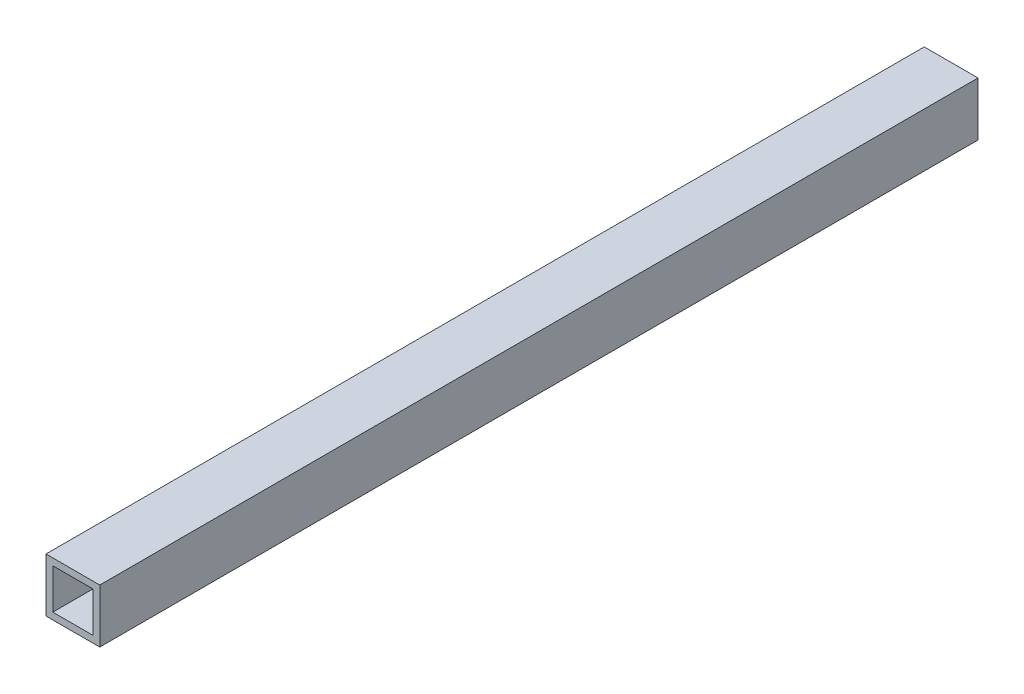
SolidWorks part; units mm, degrees
ref_plane "Front Plane" through (0, 0, 0) normal (0, 0, 1) x (1, 0, 0)
ref_plane "Top Plane" through (0, 0, 0) normal (0, 1, 0) x (1, 0, 0)
ref_plane "Right Plane" through (0, 0, 0) normal (1, 0, 0) x (0, 0, -1)
sketch "Sketch1" plane through (0, 0, 0) normal (0, 0, 1) x (1, 0, 0)
  line L1 (-6.06, 6.06) -> (6.06, 6.06)
  line L2 (-6.06, 6.06) -> (-6.06, -6.06)
  line L3 (-6.06, -6.06) -> (6.06, -6.06)
  line L4 (6.06, 6.06) -> (6.06, -6.06)
  line L5 (-6.06, 6.06) -> (6.06, -6.06) construction
  line L6 (-6.06, -6.06) -> (6.06, 6.06) construction
  line L7 (-4.53, 4.53) -> (4.53, 4.53)
  line L8 (-4.53, 4.53) -> (-4.53, -4.53)
  line L9 (-4.53, -4.53) -> (4.53, -4.53)
  line L10 (4.53, 4.53) -> (4.53, -4.53)
  line L11 (-4.53, 4.53) -> (4.53, -4.53) construction
  line L12 (-4.53, -4.53) -> (4.53, 4.53) construction
  point P0 (0, 0)
  point P6 (0, 0)
  dimension "D1" = 1.53
  dimension "D2" = 12.12
extrude "Boss-Extrude1" add sketch "Sketch1" along normal mid plane 198
equation "\"`300\"=220"
